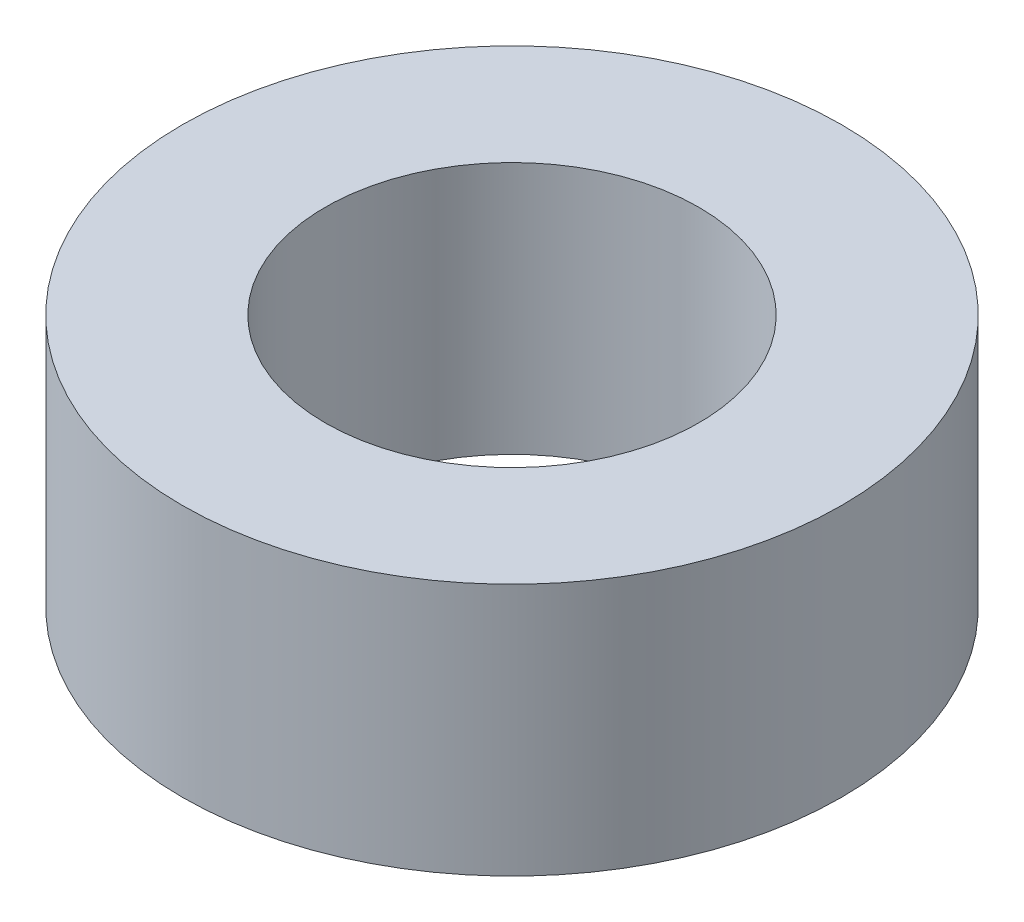
SolidWorks part; units mm, degrees
material "ABS"
ref_plane "Front Plane" through (0, 0, 0) normal (0, 0, 1) x (1, 0, 0)
ref_plane "Top Plane" through (0, 0, 0) normal (0, 1, 0) x (1, 0, 0)
ref_plane "Right Plane" through (0, 0, 0) normal (1, 0, 0) x (0, 0, -1)
sketch "Sketch1" plane through (0, 0, 0) normal (0, 1, 0) x (1, 0, 0)
  circle A0 centre (0, 0) radius 1.7
  circle A1 centre (0, 0) radius 3
  dimension "D1" = 3.4
  dimension "D2" = 6
extrude "Boss-Extrude1" add sketch "Sketch1" along normal mid plane 2.3
